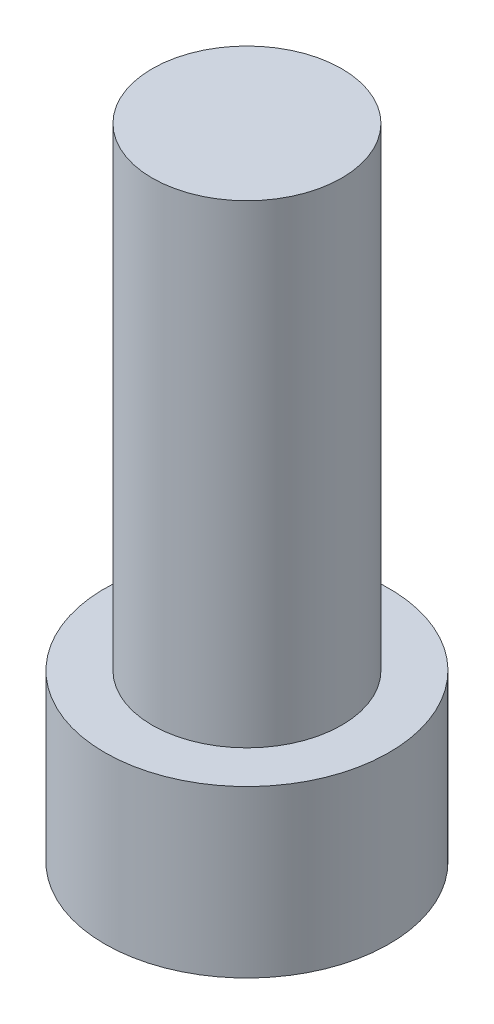
SolidWorks part; units mm, degrees
ref_plane "Front Plane" through (0, 0, 0) normal (0, 0, 1) x (1, 0, 0)
ref_plane "Top Plane" through (0, 0, 0) normal (0, 1, 0) x (1, 0, 0)
ref_plane "Right Plane" through (0, 0, 0) normal (1, 0, 0) x (0, 0, -1)
sketch "Sketch1" plane through (0, 0, 0) normal (0, 1, 0) x (1, 0, 0)
  circle A0 centre (0, 0) radius 6
  dimension "D1" = 12
extrude "Boss-Extrude1" add sketch "Sketch1" along normal blind 7
sketch "Sketch2" plane through (0, 7, 0) normal (0, 1, 0) x (-1, 0, 0)
  circle A0 centre (0, 0) radius 4
  dimension "D1" = 8
extrude "Boss-Extrude2" add sketch "Sketch2" along normal blind 20
